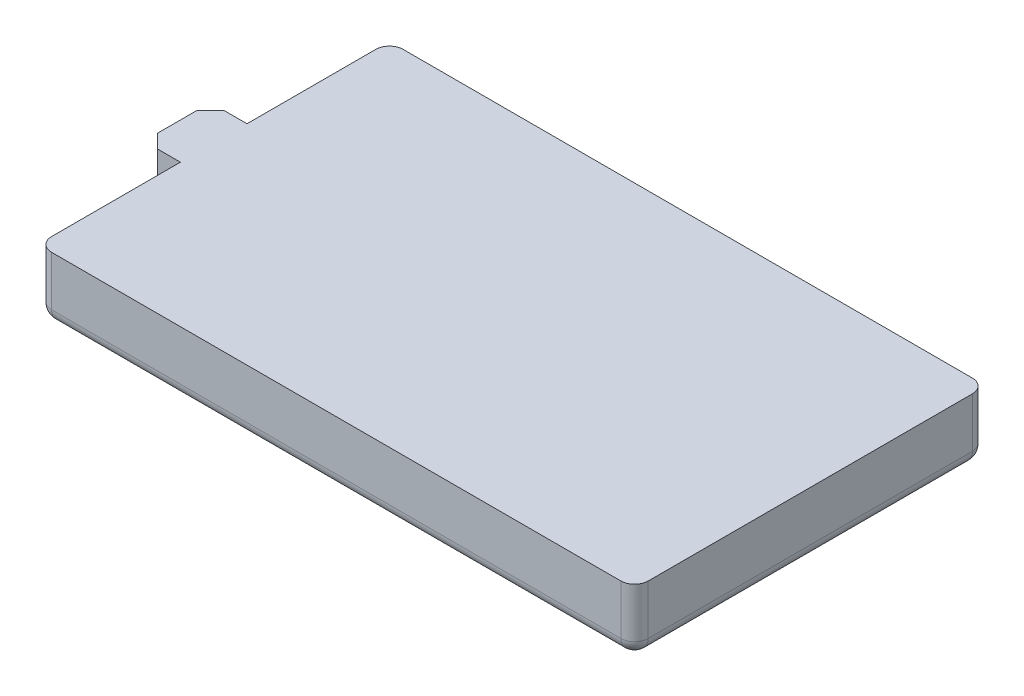
SolidWorks part; units mm, degrees
ref_plane "Front Plane" through (0, 0, 0) normal (0, 0, 1) x (1, 0, 0)
ref_plane "Top Plane" through (0, 0, 0) normal (0, 1, 0) x (1, 0, 0)
ref_plane "Right Plane" through (0, 0, 0) normal (1, 0, 0) x (0, 0, -1)
sketch "Sketch1" plane through (0, 0, 0) normal (0, 1, 0) x (1, 0, 0)
  line L0 (-55.3529, 0) -> (-62.1347, 0) construction
  line L1 (-55.3529, 32.6136) -> (55.353, 32.6136)
  line L2 (-55.3529, 32.6136) -> (-55.3529, 6.1785)
  line L3 (-55.3529, -32.6136) -> (55.353, -32.6136)
  line L4 (55.353, 32.6136) -> (55.353, -32.6136)
  line L5 (-55.3529, 32.6136) -> (55.353, -32.6136) construction
  line L6 (-55.3529, -32.6136) -> (55.353, 32.6136) construction
  line L7 (-62.1347, 0) -> (-62.1347, 6.1785)
  line L8 (-62.1347, 0) -> (-62.1347, -6.1786)
  line L9 (-62.1347, 6.1785) -> (-55.3529, 6.1785)
  line L10 (-62.1347, -6.1786) -> (-55.3529, -6.1785)
  line L11 (-55.3529, -6.1785) -> (-55.3529, -32.6136)
  point P0 (0, 0)
extrude "Boss-Extrude1" add sketch "Sketch1" along normal blind 11.7856
fillet "Fillet1" radius 2.54 9 edges at (-55.3529, 0, 19.3961) (-55.3529, 0, -19.3961) (0, 0, 32.6136) (0, 0, -32.6136) (55.353, 0, 0) (55.353, 5.8928, -32.6136) (-55.3529, 5.8928, -32.6136) (-55.3529, 5.8928, 32.6136) (55.353, 5.8928, 32.6136)
chamfer "Chamfer1" distance 2.54 angle 45 2 edges at (-62.1347, 5.8928, -6.1785) (-62.1347, 5.8928, 6.1786)
